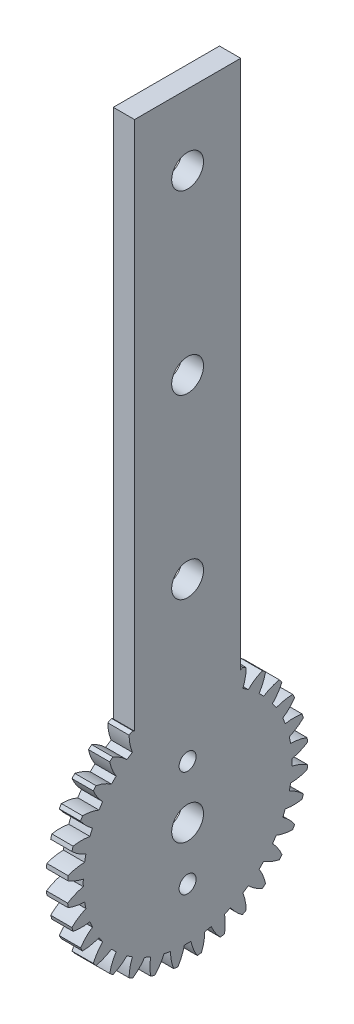
SolidWorks part; units mm, degrees
ref_plane "Plane1" through (0, 0, 0) normal (0, 0, 1) x (1, 0, 0)
ref_plane "Plane2" through (0, 0, 0) normal (0, 1, 0) x (1, 0, 0)
ref_plane "Plane3" through (0, 0, 0) normal (1, 0, 0) x (0, 0, -1)
sketch "HoldingSke" plane through (0, 0, 0) normal (0, 1, 0) x (1, 0, 0)
  line L0 (0, 0) -> (0.848, -0.5299)
  line L1 (-15, 0) -> (100, 0) construction
  line L2 (0, 0) -> (-2.1039, 2.3779)
  line L3 (0, 0) -> (-11.863, 4.5341)
  line L4 (0, 0) -> (7.3237, 4.5764)
  line L5 (0, 0) -> (-46.8476, -17.4728)
  line L6 (0, 0) -> (-2.4869, -1.6779)
  line L7 (-2.1039, 2.3779) -> (8.6586, 51.2059)
  line L8 (-76.2, 54.61) -> (-75.5, 54.61)
  line L9 (-71.009, 38.7566) -> (-53.1078, 45.2721)
  line L10 (-76.2, 71.12) -> (104.1128, 71.12)
  line L11 (0, 0) -> (-3, 0)
  line L12 (-76.2, 101.6) -> (-76.162, 101.6)
  line L13 (24.9733, 27.94) -> (52.9518, 28.4284)
  line L14 (24.9733, 27.94) -> (24.9743, 27.94)
  line L15 (24.9733, 27.94) -> (100.4006, 29.5858)
  line L16 (-63.627, -1) -> (-12.827, -1)
  circle A0 centre (0, 0) radius 2
  circle A1 centre (0, 0) radius 14.749
  circle A2 centre (0, 0) radius 37.5
  circle A3 centre (0, 0) radius 2
  dimension "MHD" = 29.498
  dimension "Hub_dia" = 75
  dimension "Bore" = 4
  dimension "MBD" = 4
  dimension "Num_teeth" = 32
  dimension "Pitch" = 1
  dimension "Overall_len" = 50
  dimension "Show_teeth" = 32
  dimension "Thickness" = 3
  dimension "OAL" = 50.0001
  dimension "T_dim" = 0.7
  dimension "Ap" = 20
  dimension "H" = 19.05
  dimension "Pitch_radius" = 180.3128
  dimension "Width" = 3
  dimension "Backlash" = 0.038
  dimension "Addendum_fac" = 1
  dimension "Dedendum_fac" = 1.25
  dimension "Clearance_fac" = 0.25
  dimension "Dedendum_add" = 0.001
  dimension "Module" = 1
sketch "BasProSke" plane through (0, 0, 0) normal (0, 1, 0) x (1, 0, 0)
  line L0 (-10, 0) -> (60, 0) construction
  line L1 (0, 0) -> (0, 17)
  line L2 (0, 0) -> (3, 0)
  line L3 (3, 0) -> (3, 17)
  line L4 (3, 17) -> (0, 17)
  dimension "Thickness" = 3
  dimension "Diameter" = 34
revolve "Base-Revolve" add sketch "BasProSke" angle 360 about L0
sketch "TooCutSke" plane through (0, 0, 0) normal (1, 0, 0) x (0, 0, -1)
  line L1 (0, 0) -> (0, 107) construction
  line L2 (0, 0) -> (-0.8516, 15.9773) construction
  line L3 (0, 0) -> (-3.1334, 31.8138) construction
  line L4 (-0.8516, 15.9773) -> (-1.5667, 15.9069) construction
  arc A0 (0.462, 14.7418) -> (-0.462, 14.7418) centre (0, 0) ccw
  arc A1 (1.3867, 16.9688) -> (-1.3867, 16.9688) centre (0, 0) ccw
  circle A2 centre (0, 0) radius 16 construction
  circle A3 centre (0, 0) radius 15.0351 construction
  arc A4 (-0.462, 14.7418) -> (-1.3867, 16.9688) centre (-6.7293, 13.4451) ccw
  arc A5 (1.3867, 16.9688) -> (0.462, 14.7418) centre (6.7293, 13.4451) ccw
  dimension "Root_dia" = 29.498
  dimension "Overcut_dia" = 34.0508
  dimension "Pitch_dia" = 32
  dimension "Base_dia" = 30.0702
  dimension "Flank_rad" = 6.4
  dimension "Half_ang" = 5.625
  dimension "Half_CT" = 0.7186
extrude "ToothCut" cut sketch "TooCutSke" along normal through all
fillet "Breaks" [suppressed] radius 0.02
fillet "RootFillets" [suppressed] radius 0.251
pattern_circular "TeethCuts" count 32 every 11.25 about axis through (-10, 0, 0) along (1, 0, 0) of "ToothCut", "RootFillets", "Breaks"
sketch "HubNeaOneSke" plane through (0, 0, 0) normal (-1, 0, 0) x (0, 0, 1)
  circle A0 centre (0, 0) radius 14.749
  dimension "Diameter" = 29.498
extrude "HubNearOne" [suppressed] add sketch "HubNeaOneSke" along normal blind 47.0001
sketch "HubNeaBotSke" plane through (0, 0, 0) normal (-1, 0, 0) x (0, 0, 1)
  circle A0 centre (0, 0) radius 14.749
  dimension "Diameter" = 29.498
extrude "HubNearBoth" [suppressed] add sketch "HubNeaBotSke" along normal blind 23.5
ref_plane "FarPln" through (3, 0, 0) normal (1, 0, 0) x (0, 0, -1)
sketch "HubFarSke" plane through (3, 0, 0) normal (1, 0, 0) x (0, 0, -1)
  circle A0 centre (0, 0) radius 14.749
  dimension "Diameter" = 29.498
extrude "HubFar" [suppressed] add sketch "HubFarSke" along normal blind 23.5
sketch "BorSke" plane through (0, 0, 0) normal (1, 0, 0) x (0, 0, -1)
  circle A0 centre (0, 0) radius 2
  dimension "Diameter" = 4
extrude "Bore" cut sketch "BorSke" along normal mid plane 100.0001
sketch "KeySke" plane through (0, 0, 0) normal (1, 0, 0) x (0, 0, -1)
  line L0 (-0.8, 0) -> (-0.8, 2.7)
  line L1 (-0.8, 2.7) -> (0.8, 2.7)
  line L2 (0.8, 2.7) -> (0.8, 0)
  line L3 (0, 0) -> (0, 34) construction
  line L4 (-0.8, 0) -> (0.8, 0)
  dimension "Offset" = 2.7
  dimension "Width" = 1.6
extrude "Keyway" [suppressed] cut sketch "KeySke" along normal mid plane 100.0001
pattern_circular "Keyway2" [suppressed] count 2 every 90 about axis through (-10, 0, 0) along (1, 0, 0)
sketch "Sketch1" plane through (3, 0, 0) normal (1, 0, 0) x (0, 0, -1)
  line L1 (7.5, 9.7886) -> (-7.5, 9.7886)
  line L2 (7.5, 9.7886) -> (7.5, 89.7886)
  line L3 (7.5, 89.7886) -> (-7.5, 89.7886)
  line L4 (-7.5, 9.7886) -> (-7.5, 89.7886)
  point P4 (0, 0)
  dimension "D1" = 15
  dimension "D2" = 80
extrude "Boss-Extrude1" add sketch "Sketch1" against normal blind 3
ref_plane "Plane4" through (3, 14.9497, 7.5) normal (0, -1, 0) x (-1, 0, 0)
hole_wizard "M4 Clearance Hole1" positions "Sketch3" profile "Sketch4" hole size "M4" standard "ANSI Metric"
sketch "Sketch3" plane through (3, 0, 0) normal (1, 0, 0) x (0, 0, -1)
  line L0 (7.5, 89.7886) -> (-7.5, 89.7886) construction
  line L1 (-7.5, 89.7886) -> (-7.5, 14.9497) construction
  point P0 (0, 79.7886)
  point P2 (0, 29.7886)
  point P9 (0, 54.7886)
  point P13 (0, 0)
  point P16 (0, 0)
  dimension "D1" = 10
  dimension "D2" = 7.5
  dimension "D3" = 7.5
  dimension "D4" = 60
  dimension "D5" = 7.5
  dimension "D6" = 25
sketch "Sketch4" plane through (3, 79.7886, 0) normal (0, 1, 0) x (0, 0, -1)
  line L0 (0, 0) -> (0, 4.3509)
  line L1 (0, 4.3509) -> (2.25, 2.999)
  line L2 (2.25, 2.999) -> (2.25, 0)
  line L5 (2.25, 0) -> (0, 0)
  line L10 (0, 4.3509) -> (-2.25, 2.999) construction
  line L11 (0, -6.35) -> (0, 107.95) construction
  dimension "Hole Dia." = 4.5
  dimension "Hole Depth" = 2.999
  dimension "Drill Angle" = 118
hole_wizard "M2 Clearance Hole1" positions "Sketch6" profile "Sketch7" hole size "M2" standard "ANSI Metric"
sketch "Sketch6" plane through (3, 0, 0) normal (1, 0, 0) x (0, 0, -1)
  point P0 (0, 7.5)
  point P2 (0, -7.5)
  point P5 (0, 0)
  point P6 (0, 0)
sketch "Sketch7" plane through (3, 7.5, 0) normal (0, 1, 0) x (0, 0, -1)
  line L0 (0, 0) -> (0, 3.72)
  line L1 (0, 3.72) -> (1.2, 2.999)
  line L2 (1.2, 2.999) -> (1.2, 0)
  line L5 (1.2, 0) -> (0, 0)
  line L10 (0, 3.72) -> (-1.2, 2.999) construction
  line L11 (0, -6.35) -> (0, 107.95) construction
  dimension "Hole Dia." = 2.4
  dimension "Hole Depth" = 2.999
  dimension "Drill Angle" = 118
equation "' \"Module@HoldingSke\" = 6.35"
equation "' \"Num_teeth@HoldingSke\" = 12"
equation "' \"Ap@HoldingSke\" =  20"
equation "' \"Ap@HoldingSke\" = 20"
equation "' \"Width@HoldingSke\" = 0.5 * 25.4"
equation "' \"Hub_dia@HoldingSke\"= 1 * 25.4"
equation "' \"Hub_dia@HoldingSke\" = 1 * 25.4"
equation "' \"Overall_len@HoldingSke\" = 1.0 * 25.4"
equation "' \"Bore@HoldingSke\" = 0.75 * 25.4"
equation "' \"T_dim@HoldingSke\" = 0.1 * 25.4"
equation "' \"Width@KeySke\" = 0.25 * 25.4"
equation "' \"Show_teeth@HoldingSke\" = 13"
equation "' \"Backlash@HoldingSke\" = 0.009 * 25.4"
equation "' \"Addendum_fac@HoldingSke\" = 1.0"
equation "' \"Dedendum_fac@HoldingSke\" = 1.25"
equation "' \"Dedendum_add@HoldingSke\" = 0.00005 * 25.4"
equation "' \"Clearance_fac@HoldingSke\" = 0.25"
equation "\"Pitch@HoldingSke\" = 1 / \"Module@HoldingSke\""
equation "\"Overcut_dia@TooCutSke\" = (\"Num_teeth@HoldingSke\" + 2 * \"Addendum_fac@HoldingSke\") / \"Pitch@HoldingSke\" + 0.002 * 25.4"
equation "\"Pitch_dia@TooCutSke\" = \"Num_teeth@HoldingSke\" / \"Pitch@HoldingSke\""
equation "\"Base_dia@TooCutSke\" = \"Num_teeth@HoldingSke\" / \"Pitch@HoldingSke\" * cos((\"Ap@HoldingSke\"  * 3.14159265 / 180))"
equation "\"Root_dia@TooCutSke\" = (\"Num_teeth@HoldingSke\" + 2) / \"Pitch@HoldingSke\" - 2 * (\"Addendum_fac@HoldingSke\" + \"Dedendum_fac@HoldingSke\") / \"Pitch@HoldingSke\" - \"Dedendum_add@HoldingSke\" * 2"
equation "\"Half_ang@TooCutSke\" = 180 / \"Num_teeth@HoldingSke\""
equation "\"Half_CT@TooCutSke\" = \"Num_teeth@HoldingSke\" / \"Pitch@HoldingSke\" * sin((3.14159265 / 2 / \"Num_teeth@HoldingSke\")) / 2 - 7 * \"Backlash@HoldingSke\" / 4"
equation "\"Flank_rad@TooCutSke\" = \"Num_teeth@HoldingSke\" / \"Pitch@HoldingSke\" / 5"
equation "\"Radius@RootFillets\" = \"Clearance_fac@HoldingSke\" / \"Pitch@HoldingSke\" + \"Dedendum_add@HoldingSke\""
equation "\"Break_rad@Breaks\" = 0.02 / \"Pitch@HoldingSke\""
equation "\"Thickness@HoldingSke\" = \"Width@HoldingSke\""
equation "\"OAL@HoldingSke\" = \"Thickness@HoldingSke\""
equation "\"MHD@HoldingSke\" = (\"Num_teeth@HoldingSke\" + 2) / \"Pitch@HoldingSke\" - 2 * (\"Addendum_fac@HoldingSke\" + \"Dedendum_fac@HoldingSke\")  / \"Pitch@HoldingSke\" - \"Dedendum_add@HoldingSke\" * 2"
equation "\"MBD@HoldingSke\" = (\"Num_teeth@HoldingSke\" + 2) / \"Pitch@HoldingSke\" - 2 * (\"Addendum_fac@HoldingSke\" + \"Dedendum_fac@HoldingSke\")  / \"Pitch@HoldingSke\" - \"Dedendum_add@HoldingSke\" * 2 - 0.002 * 25.4"
equation "\"MHD@HoldingSke\" = ((sgn( \"MHD@HoldingSke\" - \"Hub_dia@HoldingSke\" )-1)*( \"MHD@HoldingSke\" - \"Hub_dia@HoldingSke\" ))/-2+ \"Hub_dia@HoldingSke\""
equation "\"MBD@HoldingSke\" = ((sgn( \"MBD@HoldingSke\" - \"Bore@HoldingSke\" )-1)*( \"MBD@HoldingSke\" - \"Bore@HoldingSke\" ))/-2+ \"Bore@HoldingSke\""
equation "\"OAL@HoldingSke\" = ((sgn( \"OAL@HoldingSke\" - \"Overall_len@HoldingSke\" )+1)*( \"OAL@HoldingSke\" - \"Overall_len@HoldingSke\" ))/2 + \"Overall_len@HoldingSke\" + 0.000002 * 25.4"
equation "\"Num_teeth@TeethCuts\" = int( \"Show_teeth@HoldingSke\" ) + 1"
equation "\"Num_teeth@TeethCuts\" = ((sgn( \"Num_teeth@TeethCuts\" - \"Num_teeth@HoldingSke\" )-1)*( \"Num_teeth@TeethCuts\" - \"Num_teeth@HoldingSke\" ))/-2+ \"Num_teeth@HoldingSke\""
equation "\"Num_teeth@TeethCuts\" = ((sgn( \"Num_teeth@TeethCuts\" - 2.0)+1)*( \"Num_teeth@TeethCuts\" - 2.0))/2 +2.0"
equation "\"Angle@TeethCuts\" = 360.0 / \"Num_teeth@HoldingSke\""
equation "\"Diameter@BasProSke\" = (\"Num_teeth@HoldingSke\" + 2 * \"Addendum_fac@HoldingSke\") / \"Pitch@HoldingSke\""
equation "\"Thickness@BasProSke\"  = \"Thickness@HoldingSke\""
equation "' \"Fillet_rad@BasProSke\" =  \"Thickness@HoldingSke\" * 0.05"
equation "' \"Fillet_rad@BasProSke\" = \"Thickness@HoldingSke\" * 0.05"
equation "\"MHD@HoldingSke\" = ((sgn( \"MHD@HoldingSke\" - \"Root_dia@TooCutSke\" )-1)*( \"MHD@HoldingSke\" - \"Root_dia@TooCutSke\" ))/-2+ \"Root_dia@TooCutSke\""
equation "\"Diameter@HubNeaOneSke\" = \"MHD@HoldingSke\""
equation "\"Length@HubNearOne\" = \"OAL@HoldingSke\" - \"Thickness@BasProSke\""
equation "\"Diameter@HubNeaBotSke\" = \"MHD@HoldingSke\""
equation "\"Length@HubNearBoth\" = ( \"OAL@HoldingSke\" - \"Thickness@BasProSke\" ) / 2.0"
equation "\"Thickness@FarPln\" = \"Thickness@BasProSke\""
equation "\"Diameter@HubFarSke\" = \"MHD@HoldingSke\""
equation "\"Length@HubFar\" = ( \"OAL@HoldingSke\" - \"Thickness@BasProSke\" ) / 2.0"
equation "\"Diameter@BorSke\" = \"MBD@HoldingSke\""
equation "\"D1@Bore\" = \"OAL@HoldingSke\" * 2.0"
equation "\"D1@Keyway\" = \"OAL@HoldingSke\" * 2.0"
equation "\"Offset@KeySke\" = \"T_dim@HoldingSke\" + \"MBD@HoldingSke\" / 2.0"
